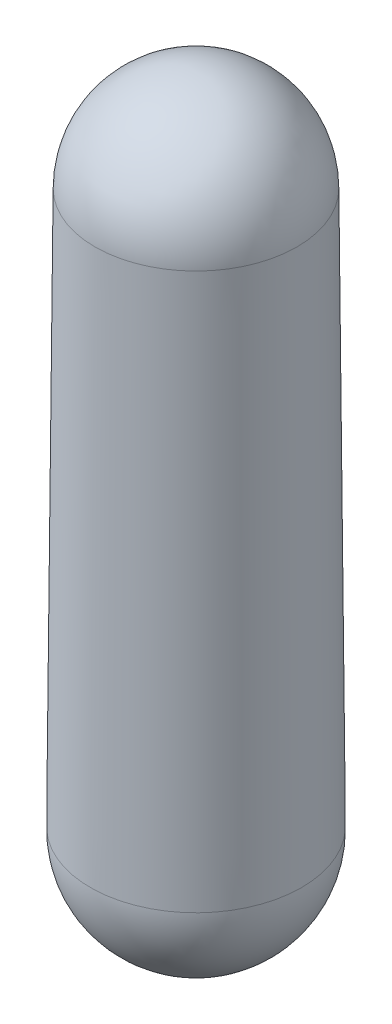
SolidWorks part; units mm, degrees
material "Nylon 101"
ref_plane "Alzado" through (0, 0, 0) normal (0, 0, 1) x (1, 0, 0)
ref_plane "Planta" through (0, 0, 0) normal (0, 1, 0) x (1, 0, 0)
ref_plane "Vista lateral" through (0, 0, 0) normal (1, 0, 0) x (0, 0, -1)
sketch "Sketch1" plane through (0, 0, 0) normal (0, 0, 1) x (1, 0, 0)
  line L0 (0, 0) -> (6.5, 0)
  line L1 (6.5, 0) -> (6.8, -35.6629)
  line L2 (6.8, -35.6629) -> (0, -35.6629)
  line L3 (0, -35.6629) -> (0, 0)
  line L4 (0, -39.6629) -> (0, 4) construction
revolve "Diafisis" add sketch "Sketch1" angle 360 about L4
sketch "Sketch2" plane through (0, 0, 0) normal (0, 0, 1) x (1, 0, 0)
  line L0 (0, -6.5) -> (0, 6.5)
  line L1 (0, -10.5) -> (0, 10.5) construction
  arc A0 (0, 6.5) -> (0, -6.5) centre (0, 0) cw
revolve "Union_proximal" add sketch "Sketch2" angle 360 about L1
sketch "Sketch3" plane through (0, 0, 0) normal (0, 0, 1) x (1, 0, 0)
  line L0 (0, -42.4629) -> (0, -28.8629)
  line L1 (0, -46.4629) -> (0, -24.8629) construction
  arc A0 (0, -28.8629) -> (0, -42.4629) centre (0, -35.6629) cw
revolve "Union_distal" add sketch "Sketch3" angle 360 about L1
